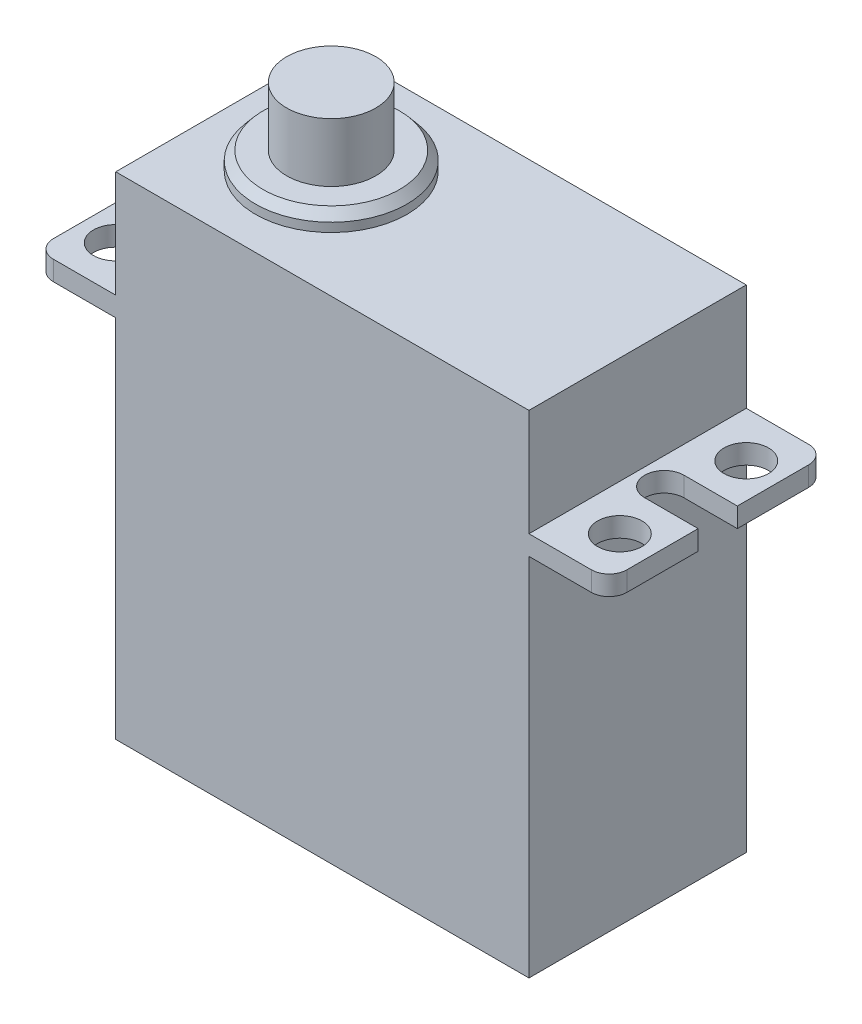
SolidWorks part; units mm, degrees
ref_plane "Front Plane" through (0, 0, 0) normal (0, 0, 1) x (1, 0, 0)
ref_plane "Top Plane" through (0, 0, 0) normal (0, 1, 0) x (1, 0, 0)
ref_plane "Right Plane" through (0, 0, 0) normal (1, 0, 0) x (0, 0, -1)
sketch "Sketch1" plane through (0, 0, 0) normal (0, 0, 1) x (1, 0, 0)
  line L0 (11.6, 7.8) -> (16.1, 7.8)
  line L1 (11.6, -13.8) -> (-11.6, -13.8)
  line L2 (11.6, -13.8) -> (11.6, 6.7)
  line L3 (11.6, 13.8) -> (-11.6, 13.8)
  line L4 (-11.6, -13.8) -> (-11.6, 6.7)
  line L5 (11.6, -13.8) -> (-11.6, 13.8) construction
  line L6 (11.6, 13.8) -> (-11.6, -13.8) construction
  line L7 (16.1, 7.8) -> (16.1, 6.7)
  line L8 (16.1, 6.7) -> (11.6, 6.7)
  line L10 (-11.6, 6.7) -> (-16.1, 6.7)
  line L11 (-16.1, 6.7) -> (-16.1, 7.8)
  line L12 (-16.1, 7.8) -> (-11.6, 7.8)
  line L13 (11.6, 7.8) -> (11.6, 13.8)
  line L14 (-11.6, 7.8) -> (-11.6, 13.8)
  point P0 (0, 0)
  dimension "D1" = 23.2
  dimension "D2" = 27.6
  dimension "D3" = 20.5
  dimension "D4" = 1.1
  dimension "D5" = 4.5
extrude "Boss-Extrude1" add sketch "Sketch1" along normal mid plane 12.2
sketch "Sketch2" plane through (0, 0, 0) normal (0, 0, 1) x (1, 0, 0)
  line L0 (-10.566, 9.7317) -> (-5.6, 9.7317) construction
  line L1 (-5.6, 9.7317) -> (-5.6, 18.1) construction
  line L2 (-5.6, 18.1) -> (-8.1, 18.1)
  line L3 (-8.1, 18.1) -> (-8.1, 14.8)
  line L4 (-8.1, 14.8) -> (-9.4305, 14.8)
  line L5 (-9.4305, 14.8) -> (-9.85, 14.3)
  line L6 (-9.85, 13.8) -> (-5.6, 13.8)
  line L7 (-5.6, 13.8) -> (-5.6, 18.1)
  line L8 (11.6, 13.8) -> (-11.6, 13.8) construction
  line L9 (-11.6, 13.8) -> (-11.6, 7.8) construction
  line L10 (-9.85, 14.3) -> (-9.85, 13.8)
  dimension "D1" = 6
  dimension "D2" = 2.5
  dimension "D3" = 4.3
  dimension "D4" = 1
  dimension "D5" = 50
  dimension "D6" = 0.5
  dimension "D7" = 4.25
revolve "Revolve1" add sketch "Sketch2" angle 360 about L7
sketch "Sketch3" plane through (0, 7.8, 0) normal (0, 1, 0) x (1, 0, 0)
  line L0 (14.15, 3.55) -> (14.15, 4.8) construction
  line L1 (14.15, 4.8) -> (14.15, 6.1) construction
  line L2 (16.1, 0) -> (13.1, 0)
  line L3 (14.7414, 3.55) -> (15.4, 3.55) construction
  line L4 (16.1, 6.1) -> (11.6, 6.1)
  line L5 (11.6, 6.1) -> (11.6, -6.1)
  line L6 (11.6, -6.1) -> (16.1, -6.1)
  line L7 (16.1, -6.1) -> (16.1, 6.1)
  line L8 (16.1, 6.1) -> (11.6, 6.1) construction
  line L9 (11.6, 6.1) -> (11.6, -6.1) construction
  line L10 (11.6, -6.1) -> (16.1, -6.1) construction
  line L11 (16.1, -6.1) -> (16.1, 6.1) construction
  line L12 (15.4, 3.55) -> (16.1, 3.55) construction
  line L13 (16.1, 1.1) -> (16.1, 0)
  line L14 (13.1, 1.1) -> (16.1, 1.1)
  line L15 (13.1, 0) -> (12, 0)
  circle A0 centre (14.15, 3.55) radius 1.25
  arc A1 (13.1, 1.1) -> (12, 0) centre (13.1, 0) ccw
  dimension "D2" = 2.5
  dimension "D3" = 1.3
  dimension "D4" = 0.7
  dimension "D5" = 1.1
  dimension "D6" = 3
  dimension "D1" = 0
extrude "Cut-Extrude1" cut sketch "Sketch3" against normal through all
mirror "Mirror4" about plane through (0, 0, 0) normal (1, 0, 0) of "Cut-Extrude1"
mirror "Mirror1" about plane through (16.1, -13.8, 0) normal (0, 0, 1) of "Mirror4", "Cut-Extrude1"
fillet "Fillet1" radius 1 4 edges at (16.1, 7.25, -6.1) (16.1, 7.25, 6.1) (-16.1, 7.25, -6.1) (-16.1, 7.25, 6.1)
